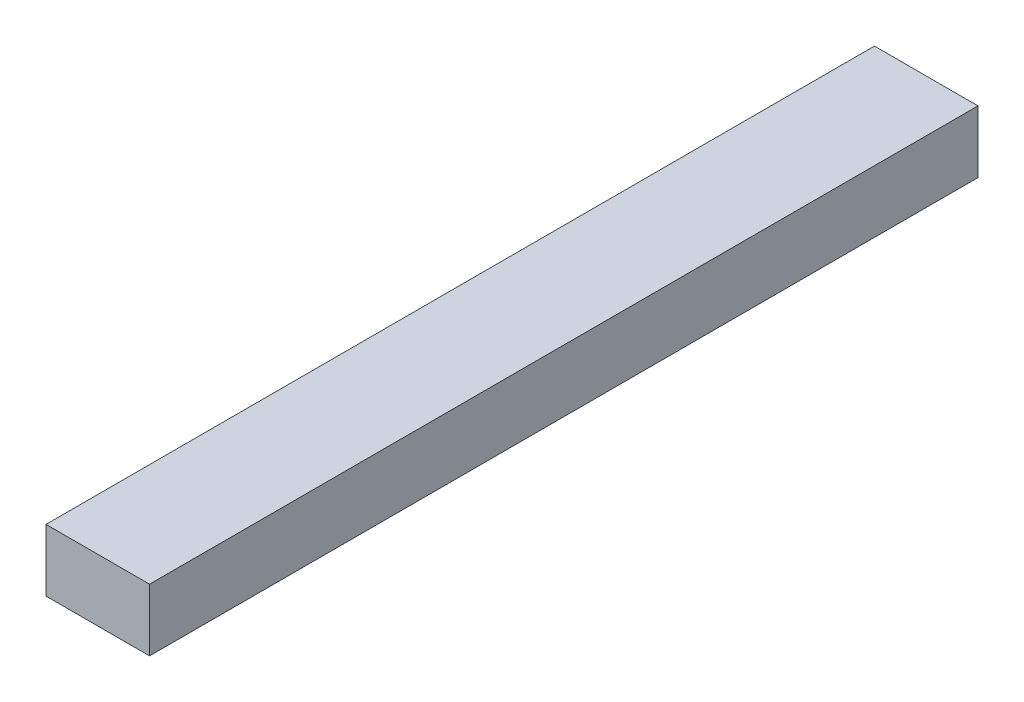
SolidWorks part; units mm, degrees
material "Kiefer"
ref_plane "Ebene vorne" through (0, 0, 0) normal (0, 0, 1) x (1, 0, 0)
ref_plane "Ebene oben" through (0, 0, 0) normal (0, 1, 0) x (1, 0, 0)
ref_plane "Ebene rechts" through (0, 0, 0) normal (1, 0, 0) x (0, 0, -1)
sketch "Skizze1" plane through (0, 0, 0) normal (0, 0, 1) x (1, 0, 0)
  line L0 (0, 0) -> (0, 40.512) construction
  line L2 (50, 30) -> (-50, 30)
  line L3 (50, 30) -> (50, -30)
  line L4 (50, -30) -> (-50, -30)
  line L5 (-50, 30) -> (-50, -30)
  line L6 (50, 30) -> (-50, -30) construction
  line L7 (50, -30) -> (-50, 30) construction
  dimension "D1" = 100
  dimension "D2" = 60
extrude "Aufsatz-Linear austragen1" add sketch "Skizze1" along normal mid plane 800
